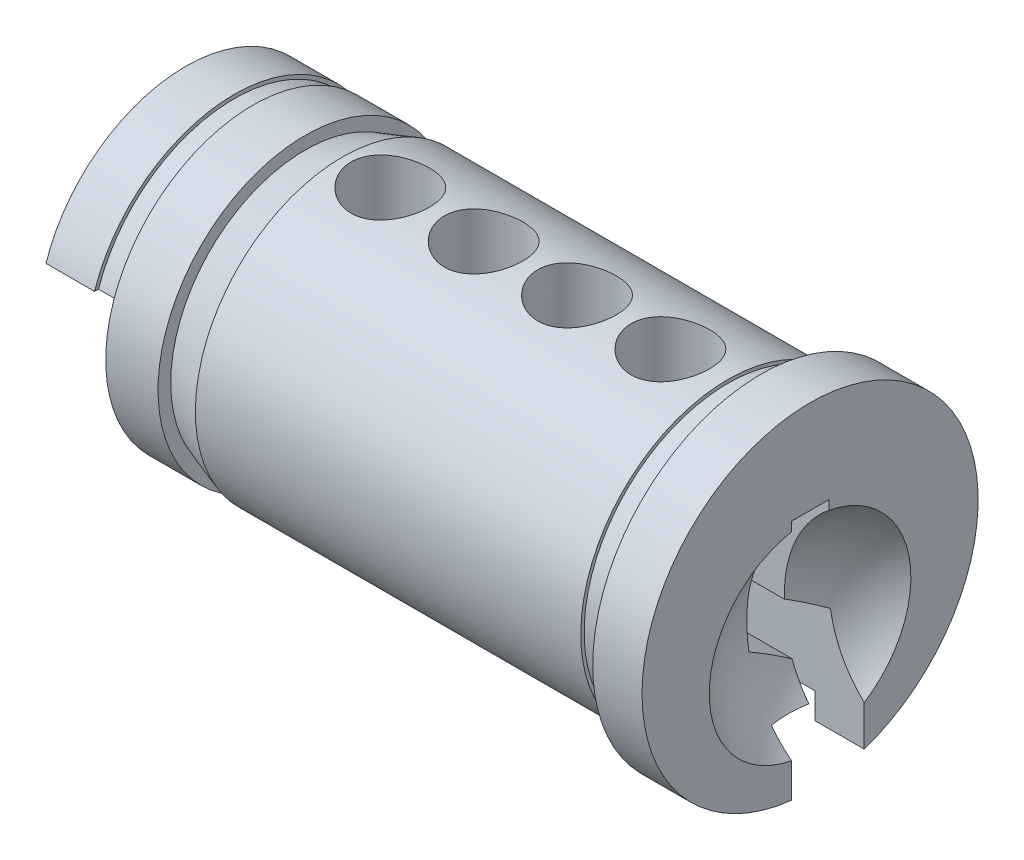
SolidWorks part; units mm, degrees
material "Brass"
ref_plane "Front" through (0, 0, 0) normal (0, 0, 1) x (1, 0, 0)
ref_plane "Top" through (0, 0, 0) normal (0, 1, 0) x (1, 0, 0)
ref_plane "Right" through (0, 0, 0) normal (1, 0, 0) x (0, 0, -1)
sketch "Sketch2" plane through (0, 0, 0) normal (1, 0, 0) x (0, 0, -1)
  circle A0 centre (0, 0) radius 5.715
  dimension "D1" = 11.43
extrude "Boss-Extrude1" add sketch "Sketch2" against normal blind 18.9484
sketch "Sketch3" plane through (0, 0, 0) normal (0, 0, 1) x (1, 0, 0)
  line L0 (0, 0) -> (-18.9484, 0) construction
  line L1 (-18.9484, 5.715) -> (-18.9484, -5.715) construction
  line L2 (-18.9484, 5.715) -> (-1.6764, 5.715)
  line L3 (0, 5.715) -> (-18.9484, 5.715) construction
  line L4 (-1.6764, 5.715) -> (-1.6764, 4.8895)
  line L5 (-1.6764, 4.8895) -> (-2.794, 4.8895)
  line L6 (-2.794, 4.8895) -> (-2.794, 5.0038)
  line L7 (-2.794, 5.0038) -> (-15.9004, 5.0038)
  line L8 (-15.9004, 5.0038) -> (-17.1704, 4.572)
  line L9 (-17.1704, 4.572) -> (-17.1704, 5.0038)
  line L10 (-17.1704, 5.0038) -> (-18.9484, 5.0038)
  line L11 (-18.9484, 5.0038) -> (-18.9484, 5.715)
  line L12 (0, -5.715) -> (0, 5.715) construction
  dimension "D1" = 10.0076
  dimension "D2" = 9.779
  dimension "D3" = 1.6764
  dimension "D4" = 1.1176
  dimension "D5" = 1.778
  dimension "D6" = 1.27
  dimension "D7" = 9.144
revolve "Cut-Revolve1" cut sketch "Sketch3" angle 360 about L0
sketch "Sketch5" plane through (-18.9484, 0, 0) normal (-1, 0, 0) x (0, 0, 1)
  line L0 (-4.7495, 1.5748) -> (4.7495, 1.5748)
  circle A0 centre (0, 0) radius 5.0038 construction
  arc A1 (4.7495, 1.5748) -> (-4.7495, 1.5748) centre (0, 0) ccw
  point P7 (0, 5.0038)
  point P8 (0, 1.5748)
  dimension "D1" = 3.429
extrude "Boss-Extrude2" add sketch "Sketch5" along normal blind 2.286
sketch "Sketch6" plane through (0, 0, 0) normal (0, 0, 1) x (1, 0, 0)
  line L0 (-18.9484, 5.0038) -> (-19.5834, 5.0038)
  line L1 (-17.1704, 5.0038) -> (-21.2344, 5.0038) construction
  line L2 (-19.5834, 5.0038) -> (-19.5834, 4.8768)
  line L3 (-19.5834, 4.8768) -> (-18.9484, 4.8768)
  line L4 (-18.9484, 4.8768) -> (-18.9484, 5.0038)
  line L5 (-18.9484, 1.5748) -> (-18.9484, -5.0038) construction
  line L6 (-21.2344, 1.5748) -> (-18.9484, 1.5748) construction
  dimension "D1" = 0.635
  dimension "D2" = 3.302
revolve "Cut-Revolve2" cut sketch "Sketch6" angle 360 about axis through (0, 0, 0) along (1, 0, 0)
sketch "Sketch7" plane through (-18.9484, 0, 0) normal (-1, 0, 0) x (0, 0, 1)
  line L0 (-2.4845, -4.3434) -> (2.4845, -4.3434)
  circle A0 centre (0, 0) radius 5.0038 construction
  arc A1 (-2.4845, -4.3434) -> (2.4845, -4.3434) centre (0, 0) ccw
  arc A2 (4.7495, 1.5748) -> (-4.7495, 1.5748) centre (0, 0) ccw construction
  point P10 (0, 5.0038)
  dimension "D1" = 9.3472
extrude "Cut-Extrude2" cut sketch "Sketch7" against normal up to surface (1.778 mm away) up to face at (-17.1704, 0, -4.572)
sketch "Sketch8" plane through (0, 0, 0) normal (1, 0, 0) x (0, 0, -1)
  line L0 (-0.635, -5.715) -> (1.8415, -5.715)
  line L1 (1.8415, -5.715) -> (1.8415, -1.8396)
  line L2 (1.8415, -1.8396) -> (0.635, -1.143)
  line L3 (0.635, -1.143) -> (0.635, 2.54)
  line L4 (0.635, 2.54) -> (-0.635, 2.54)
  line L6 (-0.635, -2.032) -> (0.635, -2.7652)
  line L7 (0.635, -2.7652) -> (0.635, -3.81)
  line L9 (-0.635, -3.81) -> (-0.635, -5.715)
  line L10 (0.635, -3.81) -> (-0.635, -3.81)
  line L11 (-0.635, 2.54) -> (-0.635, -2.032)
  line L12 (-5.715, 0) -> (-0.635, 0) construction
  line L13 (5.715, 0) -> (0.635, 0) construction
  circle A1 centre (0, 0) radius 5.715 construction
  dimension "D1" = 1.905
  dimension "D2" = 30
  dimension "D3" = 2.4765
  dimension "D4" = 1.778
  dimension "D5" = 1.2065
  dimension "D6" = 8.255
  dimension "D7" = 1.27
  dimension "D8" = 4.572
extrude "Cut-Extrude3" cut sketch "Sketch8" against normal through all
ref_plane "Plane1" through (0, 5.08, 0) normal (0, 1, 0) x (1, 0, 0)
sketch "Sketch12" plane through (0, 5.08, 0) normal (0, 1, 0) x (1, 0, 0)
  line L0 (-15.9004, 0) -> (-2.794, 0) construction
  line L1 (-4.7498, 0) -> (-7.9248, 0) construction
  line L3 (-7.9248, 0) -> (-11.0998, 0) construction
  line L4 (-11.0998, 0) -> (-14.2748, 0) construction
  line L5 (0, -5.715) -> (0, 5.715) construction
  circle A0 centre (-4.7498, 0) radius 1.3335
  circle A1 centre (-7.9248, 0) radius 1.3335
  circle A2 centre (-11.0998, 0) radius 1.3335
  circle A3 centre (-14.2748, 0) radius 1.3335
  dimension "D1" = 2.667
  dimension "D2" = 4.7498
  dimension "D3" = 3.175
extrude "Cut-Extrude4" cut sketch "Sketch12" against normal blind 6.096
sketch "Sketch13" plane through (0, 0, 0) normal (0, 0, 1) x (1, 0, 0)
  line L0 (0, 2.286) -> (0, -1.143)
  line L1 (0, -5.6796) -> (0, 5.715) construction
  line L2 (-1.524, -1.143) -> (0, -1.143)
  line L3 (-18.9484, -1.143) -> (0, -1.143) construction
  arc A1 (0, 2.286) -> (-1.524, -1.143) centre (2.5377, -0.895) ccw
  dimension "D2" = 3.429
  dimension "D1" = 1.524
revolve "Cut-Revolve3" cut sketch "Sketch13" angle 360 about L2
